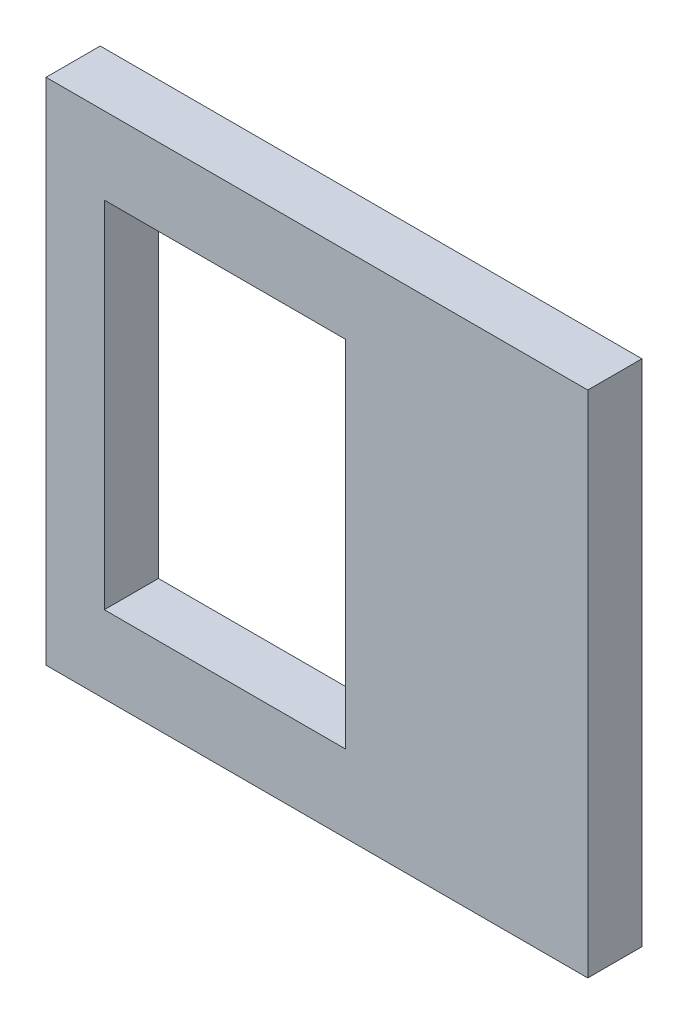
SolidWorks part; units mm, degrees
ref_plane "Front Plane" through (0, 0, 0) normal (0, 0, 1) x (1, 0, 0)
ref_plane "Top Plane" through (0, 0, 0) normal (0, 1, 0) x (1, 0, 0)
ref_plane "Right Plane" through (0, 0, 0) normal (1, 0, 0) x (0, 0, -1)
sketch "Sketch1" plane through (0, 0, 0) normal (0, 0, 1) x (1, 0, 0)
  line L1 (-50, -47) -> (50, -47)
  line L2 (-50, -47) -> (-50, 47)
  line L3 (-50, 47) -> (50, 47)
  line L4 (50, -47) -> (50, 47)
  line L5 (-50, -47) -> (50, 47) construction
  line L6 (-50, 47) -> (50, -47) construction
  point P0 (0, 0)
  dimension "D1" = 100
  dimension "D2" = 94
extrude "Boss-Extrude1" add sketch "Sketch1" along normal blind 10
sketch "Sketch2" plane through (0, 0, 10) normal (0, 0, 1) x (1, 0, 0)
  line L0 (-50, -47) -> (50, -47) construction
  line L1 (5.25, -32.75) -> (-39.25, -32.75)
  line L2 (5.25, -32.75) -> (5.25, 32.75)
  line L3 (5.25, 32.75) -> (-39.25, 32.75)
  line L4 (-39.25, -32.75) -> (-39.25, 32.75)
  line L5 (5.25, -32.75) -> (-39.25, 32.75) construction
  line L6 (5.25, 32.75) -> (-39.25, -32.75) construction
  line L7 (-50, 47) -> (-50, -47) construction
  point P0 (-17, 0)
  dimension "D1" = 65.5
  dimension "D2" = 44.5
  dimension "D3" = 14.25
  dimension "D4" = 10.75
extrude "Cut-Extrude1" cut sketch "Sketch2" against normal blind 10
